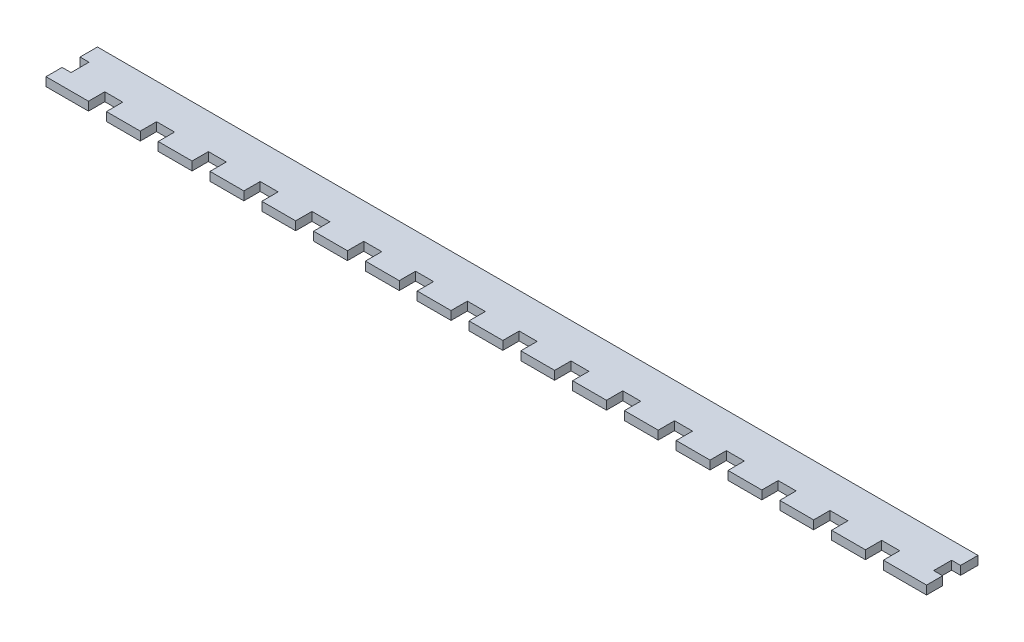
SolidWorks part; units mm, degrees
ref_plane "Front Plane" through (0, 0, 0) normal (0, 0, 1) x (1, 0, 0)
ref_plane "Top Plane" through (0, 0, 0) normal (0, 1, 0) x (1, 0, 0)
ref_plane "Right Plane" through (0, 0, 0) normal (1, 0, 0) x (0, 0, -1)
sketch "Sketch1" plane through (0, 0, 0) normal (0, 1, 0) x (1, 0, 0)
  line L2 (-323.85, -28.575) -> (-323.85, 28.575)
  line L3 (-323.85, 28.575) -> (323.85, 28.575)
  line L4 (323.85, -28.575) -> (323.85, 28.575)
  line L5 (-323.85, -28.575) -> (323.85, 28.575) construction
  line L6 (-323.85, 28.575) -> (323.85, -28.575) construction
  line L11 (-323.85, -28.575) -> (323.85, -28.575)
  point P0 (0, 0)
  dimension "D1" = 57.15
  dimension "D2" = 647.7
extrude "Boss-Extrude1" add sketch "Sketch1" along normal blind 6.35
sketch "Sketch3" plane through (0, 0, 0) normal (0, 1, 0) x (1, 0, 0)
  line L0 (-323.85, -28.575) -> (323.85, -28.575) construction
  line L2 (-317.5, -40.575) -> (-292.608, -40.575)
  line L3 (-292.608, -40.575) -> (-292.608, -28.575)
  line L4 (-292.608, -28.575) -> (-317.5, -28.575)
  line L25 (-254.508, -40.575) -> (-254.508, -28.575)
  line L26 (-254.508, -28.575) -> (-279.4, -28.575)
  line L27 (-279.4, -28.575) -> (-279.4, -40.575)
  line L28 (-279.4, -40.575) -> (-254.508, -40.575)
  line L29 (-216.408, -40.575) -> (-216.408, -28.575)
  line L30 (-216.408, -28.575) -> (-241.3, -28.575)
  line L31 (-241.3, -28.575) -> (-241.3, -40.575)
  line L32 (-241.3, -40.575) -> (-216.408, -40.575)
  line L33 (-178.308, -40.575) -> (-178.308, -28.575)
  line L34 (-178.308, -28.575) -> (-203.2, -28.575)
  line L35 (-203.2, -28.575) -> (-203.2, -40.575)
  line L36 (-203.2, -40.575) -> (-178.308, -40.575)
  line L37 (-140.208, -40.575) -> (-140.208, -28.575)
  line L38 (-140.208, -28.575) -> (-165.1, -28.575)
  line L39 (-165.1, -28.575) -> (-165.1, -40.575)
  line L40 (-165.1, -40.575) -> (-140.208, -40.575)
  line L41 (-102.108, -40.575) -> (-102.108, -28.575)
  line L42 (-102.108, -28.575) -> (-127, -28.575)
  line L43 (-127, -28.575) -> (-127, -40.575)
  line L44 (-127, -40.575) -> (-102.108, -40.575)
  line L45 (-64.008, -40.575) -> (-64.008, -28.575)
  line L46 (-64.008, -28.575) -> (-88.9, -28.575)
  line L47 (-88.9, -28.575) -> (-88.9, -40.575)
  line L48 (-88.9, -40.575) -> (-64.008, -40.575)
  line L49 (-25.908, -40.575) -> (-25.908, -28.575)
  line L50 (-25.908, -28.575) -> (-50.8, -28.575)
  line L51 (-50.8, -28.575) -> (-50.8, -40.575)
  line L52 (-50.8, -40.575) -> (-25.908, -40.575)
  line L53 (12.192, -40.575) -> (12.192, -28.575)
  line L54 (12.192, -28.575) -> (-12.7, -28.575)
  line L55 (-12.7, -28.575) -> (-12.7, -40.575)
  line L56 (-12.7, -40.575) -> (12.192, -40.575)
  line L57 (50.292, -40.575) -> (50.292, -28.575)
  line L58 (50.292, -28.575) -> (25.4, -28.575)
  line L59 (25.4, -28.575) -> (25.4, -40.575)
  line L60 (25.4, -40.575) -> (50.292, -40.575)
  line L61 (88.392, -40.575) -> (88.392, -28.575)
  line L62 (88.392, -28.575) -> (63.5, -28.575)
  line L63 (63.5, -28.575) -> (63.5, -40.575)
  line L64 (63.5, -40.575) -> (88.392, -40.575)
  line L65 (126.492, -40.575) -> (126.492, -28.575)
  line L66 (126.492, -28.575) -> (101.6, -28.575)
  line L67 (101.6, -28.575) -> (101.6, -40.575)
  line L68 (101.6, -40.575) -> (126.492, -40.575)
  line L69 (164.592, -40.575) -> (164.592, -28.575)
  line L70 (164.592, -28.575) -> (139.7, -28.575)
  line L71 (139.7, -28.575) -> (139.7, -40.575)
  line L72 (139.7, -40.575) -> (164.592, -40.575)
  line L73 (202.692, -40.575) -> (202.692, -28.575)
  line L74 (202.692, -28.575) -> (177.8, -28.575)
  line L75 (177.8, -28.575) -> (177.8, -40.575)
  line L76 (177.8, -40.575) -> (202.692, -40.575)
  line L77 (240.792, -40.575) -> (240.792, -28.575)
  line L78 (240.792, -28.575) -> (215.9, -28.575)
  line L79 (215.9, -28.575) -> (215.9, -40.575)
  line L80 (215.9, -40.575) -> (240.792, -40.575)
  line L81 (278.892, -40.575) -> (278.892, -28.575)
  line L82 (278.892, -28.575) -> (254, -28.575)
  line L83 (254, -28.575) -> (254, -40.575)
  line L84 (254, -40.575) -> (278.892, -40.575)
  line L87 (316.992, -28.575) -> (292.1, -28.575)
  line L88 (292.1, -28.575) -> (292.1, -40.575)
  line L89 (292.1, -40.575) -> (316.992, -40.575)
  line L91 (-323.85, -28.575) -> (-323.85, -40.575)
  line L92 (-323.85, -40.575) -> (-317.5, -40.575)
  line L93 (316.992, -40.575) -> (323.85, -40.575)
  line L94 (323.85, -40.575) -> (323.85, -28.575)
  line L95 (323.85, -28.575) -> (316.992, -28.575)
  line L96 (-323.85, -28.575) -> (-317.5, -28.575)
  line L97 (316.992, -40.575) -> (316.992, -28.575) [skipped]
  point P0 (-305.054, -28.575)
  dimension "D1" = 24.892
  dimension "D2" = 12
  dimension "D4" = 17
extrude "Boss-Extrude2" add sketch "Sketch3" along normal blind 6.35
sketch "Sketch4" plane through (0, 0, 0) normal (0, 1, 0) x (1, 0, 0)
  line L0 (-323.85, 28.575) -> (-323.85, -40.575) construction
  line L1 (323.85, 28.575) -> (-323.85, 28.575) construction
  line L2 (-330.454, 10.479) -> (-317.246, 10.479)
  line L3 (-330.454, 10.479) -> (-330.454, -2.729)
  line L4 (-330.454, -2.729) -> (-317.246, -2.729)
  line L5 (-317.246, 10.479) -> (-317.246, -2.729)
  line L6 (-330.454, 10.479) -> (-317.246, -2.729) construction
  line L7 (-330.454, -2.729) -> (-317.246, 10.479) construction
  line L8 (0, 0) -> (0, 63.6475) construction
  line L9 (-330.454, -15.529) -> (-317.246, -15.529)
  line L10 (-317.246, -15.529) -> (-317.246, -28.737)
  line L11 (-330.454, -28.737) -> (-317.246, -28.737)
  line L12 (-330.454, -15.529) -> (-330.454, -28.737)
  line L13 (330.454, -2.729) -> (317.246, 10.479) construction
  line L14 (330.454, 10.479) -> (317.246, -2.729) construction
  line L15 (330.454, -15.529) -> (330.454, -28.737)
  line L16 (330.454, -28.737) -> (317.246, -28.737)
  line L17 (317.246, -15.529) -> (317.246, -28.737)
  line L18 (330.454, -15.529) -> (317.246, -15.529)
  line L19 (317.246, 10.479) -> (317.246, -2.729)
  line L20 (330.454, -2.729) -> (317.246, -2.729)
  line L21 (330.454, 10.479) -> (330.454, -2.729)
  line L22 (330.454, 10.479) -> (317.246, 10.479)
  line L23 (-330.454, -41.537) -> (-317.246, -41.537)
  line L24 (-317.246, -41.537) -> (-317.246, -54.745)
  line L25 (-330.454, -54.745) -> (-317.246, -54.745)
  line L26 (-330.454, -41.537) -> (-330.454, -54.745)
  line L27 (330.454, -41.537) -> (330.454, -54.745)
  line L28 (330.454, -54.745) -> (317.246, -54.745)
  line L29 (317.246, -41.537) -> (317.246, -54.745)
  line L30 (330.454, -41.537) -> (317.246, -41.537)
  point P0 (-323.85, 3.875)
  point P1 (-323.85, 3.875)
  point P25 (323.85, 3.875)
  dimension "D1" = 13.208
  dimension "D2" = 13.208
  dimension "D3" = 24.7
  dimension "D4" = 12.8
  dimension "D6" = 12.8
  dimension "D5" = 3
extrude "Cut-Extrude2" cut sketch "Sketch4" along normal through all
sketch "Sketch5" plane through (0, 0, -28.575) normal (0, 0, -1) x (-1, 0, 0)
  line L4 (-323.85, 0) -> (323.85, 0)
  line L5 (323.85, 0) -> (323.85, 6.35)
  line L6 (323.85, 6.35) -> (-323.85, 6.35)
  line L7 (-323.85, 6.35) -> (-323.85, 0)
  line L8 (-323.85, 0) -> (323.85, 0)
  line L9 (323.85, 0) -> (323.85, 6.35)
  line L10 (323.85, 6.35) -> (-323.85, 6.35)
  line L11 (-323.85, 6.35) -> (-323.85, 0)
  dimension "D1" = 0
extrude "Cut-Extrude3" cut sketch "Sketch5" against normal up to surface (31.304 mm away) up to face at (320.548, 3.175, 2.729)
